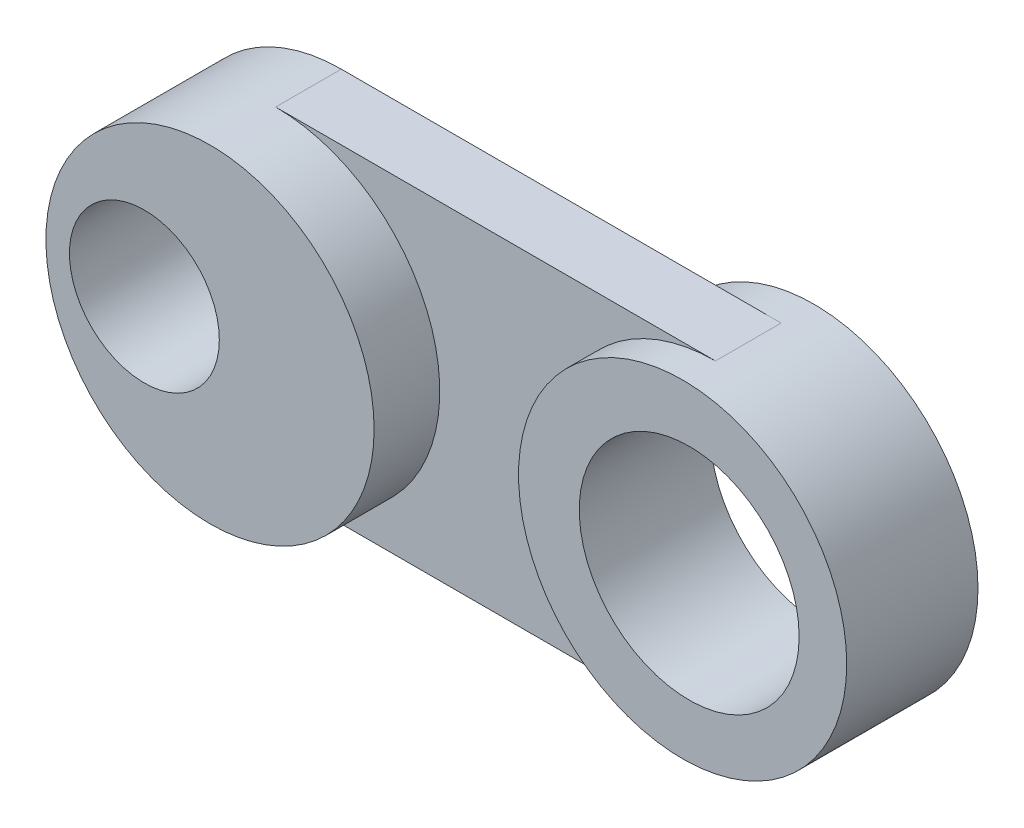
SolidWorks part; units mm, degrees
material "Custom Plastic"
ref_plane "Front Plane" through (0, 0, 0) normal (0, 0, 1) x (1, 0, 0)
ref_plane "Top Plane" through (0, 0, 0) normal (0, 1, 0) x (1, 0, 0)
ref_plane "Right Plane" through (0, 0, 0) normal (1, 0, 0) x (0, 0, -1)
sketch "Sketch1" plane through (0, 0, 0) normal (0, 0, 1) x (1, 0, 0)
  line L0 (0, 12.7) -> (17.018, 12.7)
  line L1 (0, 0) -> (17.018, 0)
  arc A0 (0, 0) -> (0, 12.7) centre (0, 6.35) cw
  arc A1 (17.018, 12.7) -> (17.018, 0) centre (17.018, 6.35) cw
  circle A2 centre (-2.54, 6.35) radius 2.9
  circle A3 centre (17.272, 6.35) radius 4.2545
  dimension "D1" = 6.35
  dimension "D2" = 17.018
  dimension "D3" = 5.8
  dimension "D4" = 2.54
  dimension "D7" = 8.509
  dimension "D5" = 0.254
  dimension "D6" = 6.35
extrude "Boss-Extrude1" add sketch "Sketch1" along normal mid plane 2.54
sketch "Sketch2" plane through (0, 0, 1.27) normal (0, 0, 1) x (1, 0, 0)
  circle A0 centre (0, 6.35) radius 6.35
  arc A1 (0, 12.7) -> (0, 0) centre (0, 6.35) ccw construction
  arc M2 (0, 12.7) -> (0, 0) centre (0, 6.35) ccw
  circle M7 centre (-2.54, 6.35) radius 2.9
extrude "Boss-Extrude2" add sketch "Sketch2" along normal blind 2.54 contours A0 M2 M7
sketch "Sketch3" plane through (0, 0, 3.81) normal (0, 0, 1) x (1, 0, 0)
  line L0 (-2.9035, 3.4729) -> (-2.54, 3.55)
  line L1 (-2.54, 3.55) -> (-2.1765, 3.4729)
  line L4 (-2.54, 9.25) -> (-2.54, 3.45) construction
  line L5 (-3.2363, 3.638) -> (-2.9035, 3.4729)
  line L6 (-3.6076, 3.6536) -> (-3.2363, 3.638)
  line L7 (-3.8889, 3.8963) -> (-3.6076, 3.6536)
  line L8 (-4.2446, 4.0039) -> (-3.8889, 3.8963)
  line L9 (-4.4567, 4.3089) -> (-4.2446, 4.0039)
  line L10 (-4.7745, 4.5015) -> (-4.4567, 4.3089)
  line L11 (-4.9041, 4.8497) -> (-4.7745, 4.5015)
  line L12 (-5.164, 5.1152) -> (-4.9041, 4.8497)
  line L13 (-5.203, 5.4848) -> (-5.164, 5.1152)
  line L14 (-5.3886, 5.8066) -> (-5.203, 5.4848)
  line L15 (-5.3345, 6.1742) -> (-5.3886, 5.8066)
  line L16 (-5.4343, 6.5321) -> (-5.3345, 6.1742)
  line L17 (-5.2904, 6.8747) -> (-5.4343, 6.5321)
  line L18 (-5.2981, 7.2461) -> (-5.2904, 6.8747)
  line L19 (-5.0735, 7.5422) -> (-5.2981, 7.2461)
  line L20 (-4.9886, 7.9039) -> (-5.0735, 7.5422)
  line L21 (-4.6974, 8.1348) -> (-4.9886, 7.9039)
  line L22 (-4.5252, 8.464) -> (-4.6974, 8.1348)
  line L23 (-4.1858, 8.6152) -> (-4.5252, 8.464)
  line L24 (-3.9371, 8.8913) -> (-4.1858, 8.6152)
  line L25 (-3.5707, 8.9534) -> (-3.9371, 8.8913)
  line L26 (-3.2612, 9.1589) -> (-3.5707, 8.9534)
  line L27 (-2.8909, 9.1279) -> (-3.2612, 9.1589)
  line L28 (-2.54, 9.25) -> (-2.8909, 9.1279)
  line L29 (-2.1891, 9.1279) -> (-2.54, 9.25)
  line L30 (-1.8188, 9.1589) -> (-2.1891, 9.1279)
  line L31 (-1.5093, 8.9534) -> (-1.8188, 9.1589)
  line L32 (-1.1429, 8.8913) -> (-1.5093, 8.9534)
  line L33 (-0.8942, 8.6152) -> (-1.1429, 8.8913)
  line L34 (-0.5548, 8.464) -> (-0.8942, 8.6152)
  line L35 (-0.3826, 8.1348) -> (-0.5548, 8.464)
  line L36 (-0.0914, 7.9039) -> (-0.3826, 8.1348)
  line L37 (-0.0065, 7.5422) -> (-0.0914, 7.9039)
  line L38 (0.2181, 7.2461) -> (-0.0065, 7.5422)
  line L39 (0.2104, 6.8747) -> (0.2181, 7.2461)
  line L40 (0.3543, 6.5321) -> (0.2104, 6.8747)
  line L41 (0.2545, 6.1742) -> (0.3543, 6.5321)
  line L42 (0.3086, 5.8066) -> (0.2545, 6.1742)
  line L43 (0.123, 5.4848) -> (0.3086, 5.8066)
  line L44 (0.084, 5.1152) -> (0.123, 5.4848)
  line L45 (-0.1759, 4.8497) -> (0.084, 5.1152)
  line L46 (-0.3055, 4.5015) -> (-0.1759, 4.8497)
  line L47 (-0.6233, 4.3089) -> (-0.3055, 4.5015)
  line L48 (-0.8354, 4.0039) -> (-0.6233, 4.3089)
  line L49 (-1.1911, 3.8963) -> (-0.8354, 4.0039)
  line L50 (-1.4724, 3.6536) -> (-1.1911, 3.8963)
  line L51 (-1.8437, 3.638) -> (-1.4724, 3.6536)
  line L52 (-2.1765, 3.4729) -> (-1.8437, 3.638)
  circle A0 centre (-2.54, 6.35) radius 2.9 construction
  circle A1 centre (-2.54, 6.35) radius 2.8 construction
  point P83 (-2.54, 6.35)
  circle M5 centre (-2.54, 6.35) radius 2.9
  dimension "D2" = 5.6
  dimension "D1" = 25
extrude "Boss-Extrude3" [suppressed] add sketch "Sketch3" against normal up to surface (5.08 mm away) contours L22 L21 M5 | L20 L19 M5 | L18 L17 M5 | L16 L15 M5 | L14 L13 M5 | L12 L11 M5 | L10 L9 M5 | L8 L7 M5 | L6 L5 M5 | L1 L0 M5 | L52 L51 M5 | L50 L49 M5 | L48 L47 M5 | L46 L45 M5 | L44 L43 M5 | L42 L41 M5 | L40 L39 M5 | L38 L37 M5 | L36 L35 M5 | L34 L33 M5 | L32 L31 M5 | L30 L29 M5 | L28 L27 M5 | L26 L25 M5 | L24 L23 M5
sketch "Sketch4" plane through (0, 0, 0) normal (0, 0, 1) x (1, 0, 0)
  circle A0 centre (17.272, 6.35) radius 4.2545
  circle A1 centre (17.272, 6.35) radius 4.2545 construction
  circle A2 centre (17.018, 6.35) radius 6.35
  arc A3 (17.018, 0) -> (17.018, 12.7) centre (17.018, 6.35) ccw construction
extrude "Boss-Extrude4" add sketch "Sketch4" along normal mid plane 5.08
